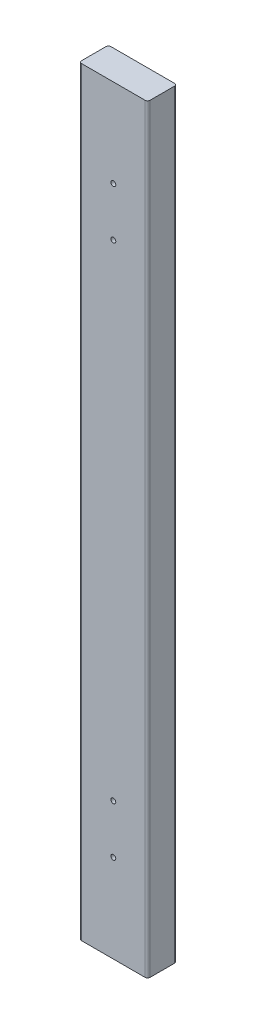
SolidWorks part; units mm, degrees
ref_plane "Front" through (0, 0, 0) normal (0, 0, 1) x (1, 0, 0)
ref_plane "Top" through (0, 0, 0) normal (0, 1, 0) x (1, 0, 0)
ref_plane "Right" through (0, 0, 0) normal (1, 0, 0) x (0, 0, -1)
sketch "Sketch1" plane through (0, 0, 0) normal (0, 1, 0) x (1, 0, 0)
  line L1 (44.45, 19.05) -> (-44.45, 19.05)
  line L2 (44.45, 19.05) -> (44.45, -19.05)
  line L3 (44.45, -19.05) -> (-44.45, -19.05)
  line L4 (-44.45, 19.05) -> (-44.45, -19.05)
  line L5 (44.45, 19.05) -> (-44.45, -19.05) construction
  line L6 (44.45, -19.05) -> (-44.45, 19.05) construction
  point P0 (0, 0)
  dimension "D1" = 88.9
  dimension "D2" = 38.1
extrude "Boss-Extrude1" add sketch "Sketch1" along normal blind 985.8375
fillet "Fillet1" radius 3.175 4 edges at (44.45, 492.9187, -19.05) (-44.45, 492.9187, -19.05) (44.45, 492.9187, 19.05) (-44.45, 492.9187, 19.05)
hole_wizard "1/4 (0.25) Diameter Hole1" positions "Sketch2" profile "Sketch3" hole size "1/4" standard "ANSI Inch" end condition through all
sketch "Sketch2" plane through (0, 0, 19.05) normal (0, 0, 1) x (1, 0, 0)
  line L0 (-44.45, 0) -> (-44.45, 985.8375) construction
  line L1 (-41.275, 0) -> (41.275, 0) construction
  line L2 (-41.275, 985.8375) -> (41.275, 985.8375) construction
  point P0 (0, 114.3)
  point P2 (0, 177.8)
  point P4 (0, 808.0375)
  point P5 (0, 871.5375)
  dimension "D1" = 44.45
  dimension "D2" = 114.3
  dimension "D3" = 63.5
  dimension "D4" = 114.3
  dimension "D5" = 63.5
  dimension "D6" = 44.45
sketch "Sketch3" plane through (0, 114.3, 19.05) normal (1, 0, 0) x (0, -1, 0)
  line L0 (0, 0) -> (0, 38.1)
  line L1 (0, 38.1) -> (3.175, 38.1)
  line L2 (3.175, 38.1) -> (3.175, 0)
  line L5 (3.175, 0) -> (0, 0)
  line L11 (0, -6.35) -> (0, 107.95) construction
  dimension "Thru Hole Dia." = 6.35
  dimension "Thru Hole Depth" = 38.1
